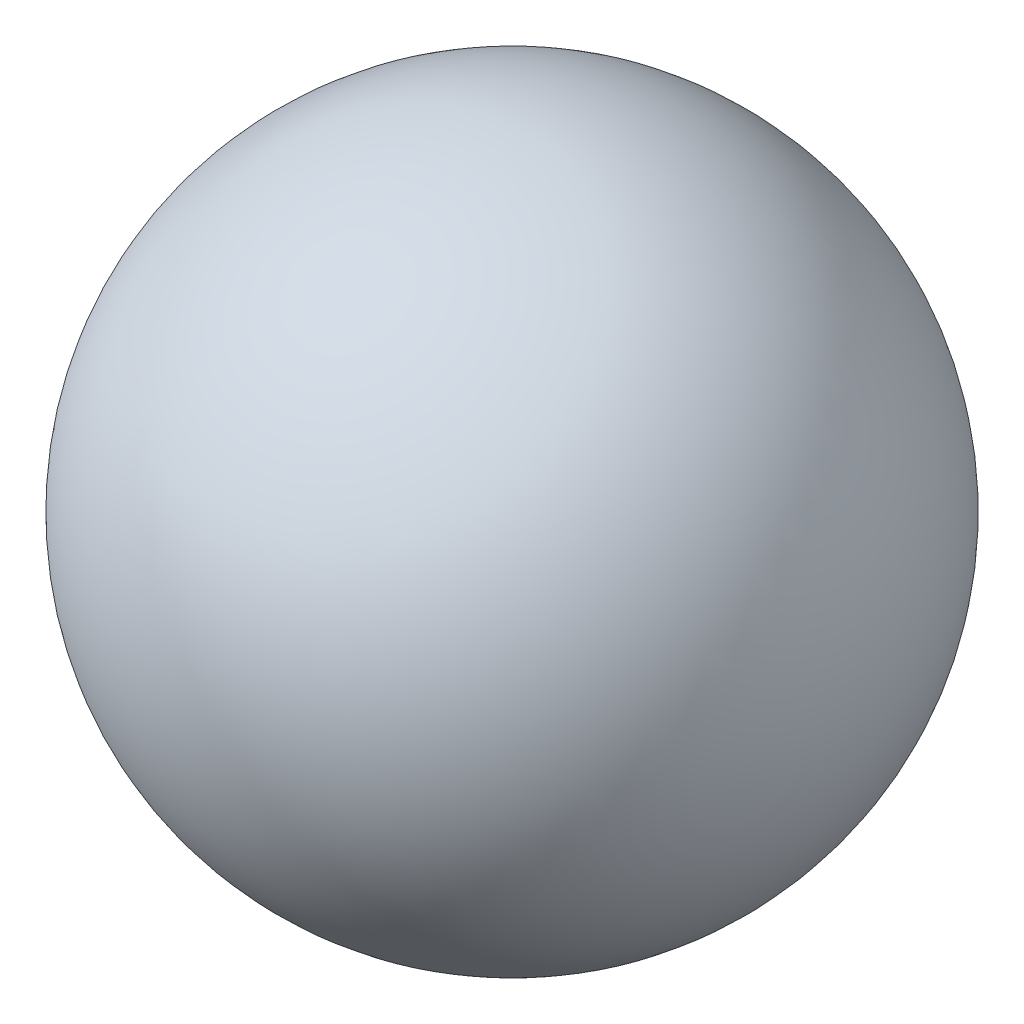
SolidWorks part; units mm, degrees
material "1023 Carbon Steel Sheet (SS)"
ref_plane "Front Plane" through (0, 0, 0) normal (0, 0, 1) x (1, 0, 0)
ref_plane "Top Plane" through (0, 0, 0) normal (0, 1, 0) x (1, 0, 0)
ref_plane "Right Plane" through (0, 0, 0) normal (1, 0, 0) x (0, 0, -1)
sketch "Sketch1" plane through (0, 0, 0) normal (0, 0, 1) x (1, 0, 0)
  circle A0 centre (0, 0) radius 0.3302
  dimension "Dia" = 0.6604
sketch "Sketch2" plane through (0, 0, 0) normal (0, 0, 1) x (1, 0, 0)
  line L0 (0, 0.3302) -> (0, -0.3302)
  circle A0 centre (0, 0) radius 0.3302 construction
  arc A1 (0, 0.3302) -> (0, -0.3302) centre (0, 0) cw
revolve "Revolve1" add sketch "Sketch2" angle 360 about L0
